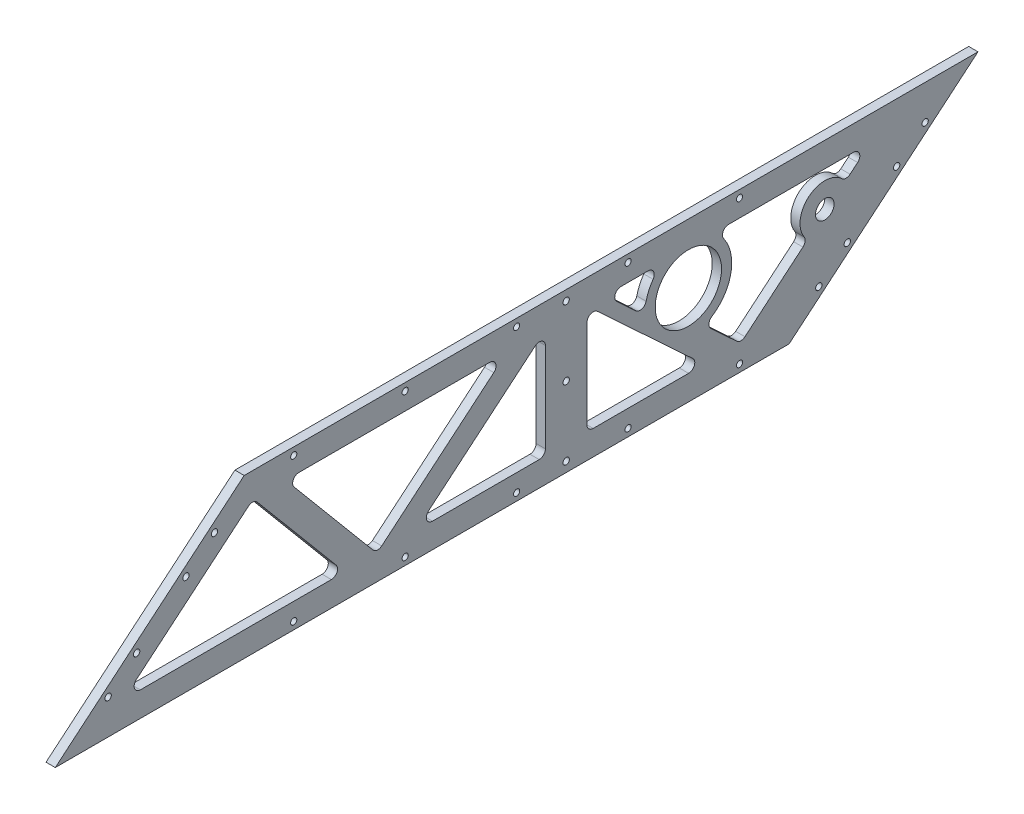
SolidWorks part; units mm, degrees
material "6061-T6 (SS)"
ref_plane "Front Plane" through (0, 0, 0) normal (0, 0, 1) x (1, 0, 0)
ref_plane "Top Plane" through (0, 0, 0) normal (0, 1, 0) x (1, 0, 0)
ref_plane "Right Plane" through (0, 0, 0) normal (1, 0, 0) x (0, 0, -1)
sketch "Sketch1" plane through (0, 0, 0) normal (1, 0, 0) x (0, 0, -1)
  line L0 (0, 12.7) -> (0, -12.7) construction
  line L1 (0, -12.7) -> (33.2976, -40.64) construction
  line L2 (33.2976, -40.64) -> (312.6976, -40.64)
  line L3 (312.6976, -40.64) -> (345.9952, -12.7)
  line L4 (345.9952, -12.7) -> (345.9952, 12.7) construction
  line L5 (345.9952, 12.7) -> (312.6976, 40.64) construction
  line L6 (312.6976, 40.64) -> (33.2976, 40.64)
  line L7 (33.2976, 40.64) -> (0, 12.7)
  line L8 (33.2976, 40.64) -> (33.2976, -40.64) construction
  line L9 (312.6976, 40.64) -> (312.6976, -40.64) construction
  line L10 (0, 0) -> (345.9952, 0) construction
  line L11 (0, 12.7) -> (-63.5681, -40.64)
  line L12 (-63.5681, -40.64) -> (33.2976, -40.64)
  line L13 (312.6976, 40.64) -> (409.5633, 40.64)
  line L14 (409.5633, 40.64) -> (345.9952, -12.7)
  point P10 (33.2976, 0)
  point P12 (312.6976, 0)
  dimension "D1" = 81.28
  dimension "D2" = 279.4
  dimension "D3" = 25.4
  dimension "D4" = 40
extrude "Boss-Extrude1" add sketch "Sketch1" along normal blind 4.7625
sketch "Sketch2" plane through (4.7625, 0, 0) normal (1, 0, 0) x (0, 0, -1)
  line L0 (-3.2177, 10) -> (373.048, 10) construction
  line L1 (312.6976, -40.64) -> (409.5633, 40.64) construction
  line L2 (345.048, 10) -> (245.048, 10) construction
  line L3 (245.048, -5) -> (345.048, -5) construction
  line L4 (245.048, -5) -> (245.048, 25) construction
  line L5 (245.048, 25) -> (345.048, 25) construction
  line L6 (345.048, -5) -> (345.048, 25) construction
  line L7 (33.2976, 40.64) -> (-63.5681, -40.64) construction
  line L9 (0, 0) -> (361.1305, 0) construction
  circle A0 centre (300.048, 10) radius 6.9977 construction
  circle A1 centre (282.2147, 8) radius 1.4986 construction
  circle A2 centre (270.2178, 15.9334) radius 0.9906 construction
  circle A3 centre (282.2147, 8) radius 11.4777 construction
  circle A4 centre (270.2178, 15.9334) radius 7.1501 construction
  circle A5 centre (300.048, 10) radius 12.827 construction
  circle A6 centre (261.048, 10) radius 17
  circle A7 centre (282.2147, 8) radius 5.1181 construction
  circle A8 centre (331.0042, 10) radius 4.7625
  point P11 (300.048, 10)
  point P12 (282.2147, 8)
  point P13 (270.2178, 15.9334)
  point P23 (261.048, 10)
  dimension "D5" = 13.9954
  dimension "D6" = 2.9972
  dimension "D7" = 1.9812
  dimension "D8" = 25.654
  dimension "D9" = 22.9553
  dimension "D10" = 14.3002
  dimension "D12" = 34
  dimension "D13" = 10.2362
  dimension "D17" = 9.525
  dimension "D1" = 17.9451
  dimension "D2" = 14.3828
  dimension "D3" = 30
  dimension "D4" = 100
  dimension "D11" = 10.922
  dimension "D14" = 16
  dimension "D15" = 13
  dimension "D16" = 55
  dimension "D18" = 30.9562
  dimension "D19" = 28
  dimension "D20" = 10
extrude "Gearbox (with Press fits)" cut sketch "Sketch2" against normal through all
sketch "Sketch3" plane through (4.7625, 0, 0) normal (1, 0, 0) x (0, 0, -1)
  line L0 (0, 0) -> (361.1305, 0) construction
  line L1 (28.757, 36.83) -> (405.0227, 36.83) construction
  line L2 (33.2976, 40.64) -> (-63.5681, -40.64) construction
  line L5 (409.5633, 40.64) -> (33.2976, 40.64) construction
  line L6 (312.6976, -40.64) -> (409.5633, 40.64) construction
  circle A0 centre (287.2976, 36.83) radius 1.5811
  circle A1 centre (230.1476, 36.83) radius 1.5811
  circle A2 centre (172.9976, 36.83) radius 1.5811
  circle A3 centre (115.8476, 36.83) radius 1.5811
  circle A4 centre (58.6976, 36.83) radius 1.5812
  circle A5 centre (58.6976, -36.83) radius 1.5812
  circle A6 centre (115.8476, -36.83) radius 1.5811
  circle A7 centre (172.9976, -36.83) radius 1.5811
  circle A8 centre (230.1476, -36.83) radius 1.5811
  circle A9 centre (287.2976, -36.83) radius 1.5811
  dimension "D1" = 3.1623
  dimension "D2" = 25.4
  dimension "D3" = 3.81
  dimension "D4" = 5
extrude "Cut-Extrude1" cut sketch "Sketch3" against normal through all
hole_wizard "#2 Clearance Hole1" positions "Sketch6" profile "Sketch5" hole size "#2" standard "ANSI Inch"
sketch "Sketch6" plane through (4.7625, 0, 0) normal (1, 0, 0) x (0, 0, -1)
  line L0 (241.1305, 40.64) -> (241.1305, -40.64) construction
  line L1 (409.5633, 40.64) -> (33.2976, 40.64) construction
  line L2 (-63.5681, -40.64) -> (312.6976, -40.64) construction
  line L4 (244.1305, 40.64) -> (244.1305, -40.64) construction
  line L6 (241.1305, -16) -> (342.0624, -16) construction
  line L7 (312.6976, -40.64) -> (409.5633, 40.64) construction
  line L9 (241.1305, -13) -> (345.6377, -13) construction
  line L11 (241.1305, 13) -> (376.6233, 13) construction
  line L12 (308.1305, 13) -> (308.1305, -13) construction
  circle A0 centre (257.1305, 0) radius 14 construction
  point P28 (267.1305, -13)
  point P30 (308.1305, -13)
  point P32 (244.1305, -13)
  point P34 (244.1305, 13)
  point P36 (275.1305, 13)
  point P38 (308.1305, 13)
  dimension "D1" = 3
  dimension "D2" = 3
  dimension "D3" = 26
  dimension "D4" = 29
  dimension "D5" = 16
  dimension "D6" = 16
  dimension "D7" = 67
  dimension "D8" = 34
sketch "Sketch5" plane through (4.7625, -13, -267.1305) normal (0, 1, 0) x (0, 0, -1)
  line L0 (0, 0) -> (0, 5.5586)
  line L1 (0, 5.5586) -> (1.2192, 4.826)
  line L2 (1.2192, 4.826) -> (1.2192, 0)
  line L5 (1.2192, 0) -> (0, 0)
  line L10 (0, 5.5586) -> (-1.2192, 4.826) construction
  line L11 (0, -6.35) -> (0, 107.95) construction
  dimension "Hole Dia." = 2.4384
  dimension "Hole Depth" = 4.826
  dimension "Drill Angle" = 118
hole_wizard "#4 Clearance Hole2" positions "Sketch8" profile "Sketch9" hole size "#4" standard "ANSI Inch"
sketch "Sketch8" plane through (4.7625, 0, 0) normal (1, 0, 0) x (0, 0, -1)
  line L0 (-15.1353, 0) -> (361.1305, 0) construction
  line L1 (33.2976, 40.64) -> (-63.5681, -40.64) construction
  line L2 (312.6976, -40.64) -> (409.5633, 40.64) construction
  line L4 (403.636, 40.64) -> (306.7703, -40.64) construction
  line L5 (409.5633, 40.64) -> (33.2976, 40.64) construction
  line L6 (-63.5681, -40.64) -> (312.6976, -40.64) construction
  line L8 (39.2249, 40.64) -> (-57.6408, -40.64) construction
  line L10 (355.2032, 0) -> (-9.208, 0) construction
  line L11 (327.9626, -22.8575) -> (-36.4485, -22.8575) construction
  line L13 (342.5558, -10.6124) -> (-21.8554, -10.6124) construction
  line L15 (3.4394, 10.6124) -> (367.8505, 10.6124) construction
  line L17 (18.0326, 22.8575) -> (382.4437, 22.8575) construction
  point P25 (327.9626, -22.8575)
  point P27 (342.5558, -10.6124)
  point P29 (367.8505, 10.6124)
  point P31 (382.4437, 22.8575)
  point P34 (-36.4485, -22.8575)
  point P36 (-21.8554, -10.6124)
  point P38 (3.4394, 10.6124)
  point P40 (18.0326, 22.8575)
  dimension "D1" = 16.51
  dimension "D2" = 19.05
  dimension "D3" = 16.51
  dimension "D4" = 19.05
  dimension "D5" = 3.81
  dimension "D6" = 3.81
sketch "Sketch9" plane through (4.7625, -22.8575, -327.9626) normal (0, 1, 0) x (0, 0, -1)
  line L0 (0, 0) -> (0, 29.6826)
  line L1 (0, 29.6826) -> (1.6319, 28.702)
  line L2 (1.6319, 28.702) -> (1.6319, 0)
  line L5 (1.6319, 0) -> (0, 0)
  line L10 (0, 29.6826) -> (-1.632, 28.702) construction
  line L11 (0, -6.35) -> (0, 107.95) construction
  dimension "Hole Dia." = 3.2639
  dimension "Hole Depth" = 28.702
  dimension "Drill Angle" = 118
hole_wizard "#4 Clearance Hole1" positions "Sketch11" profile "Sketch10" hole size "#4" standard "ANSI Inch"
sketch "Sketch11" plane through (4.7625, 0, 0) normal (1, 0, 0) x (0, 0, -1)
  line L0 (27.2435, 35.56) -> (403.5092, 35.56) construction
  line L1 (33.2976, 40.64) -> (-63.5681, -40.64) construction
  line L2 (312.6976, -40.64) -> (409.5633, 40.64) construction
  line L4 (-15.1353, 0) -> (361.1305, 0) construction
  line L5 (198.3976, 35.56) -> (198.3976, -35.56) construction
  line L6 (409.5633, 40.64) -> (33.2976, 40.64) construction
  point P12 (198.3976, 35.56)
  point P15 (198.3976, -35.56)
  point P20 (198.3976, 0)
  dimension "D1" = 5.08
  dimension "D2" = 165.1
sketch "Sketch10" plane through (4.7625, 35.56, -198.3976) normal (0, 1, 0) x (0, 0, -1)
  line L0 (0, 0) -> (0, 5.8066)
  line L1 (0, 5.8066) -> (1.6319, 4.826)
  line L2 (1.6319, 4.826) -> (1.6319, 0)
  line L5 (1.6319, 0) -> (0, 0)
  line L10 (0, 5.8066) -> (-1.6319, 4.826) construction
  line L11 (0, -6.35) -> (0, 107.95) construction
  dimension "Hole Dia." = 3.2639
  dimension "Hole Depth" = 4.826
  dimension "Drill Angle" = 118
sketch "Sketch12" plane through (4.7625, 0, 0) normal (1, 0, 0) x (0, 0, -1)
  line L0 (-21.9928, -22.3328) -> (35.4878, 25.8991)
  line L1 (39.9609, 25.5078) -> (80.4323, -22.7241)
  line L2 (78.0001, -27.94) -> (-19.9519, -27.94)
  line L3 (209.0547, 20.6605) -> (209.0547, -24.765)
  line L4 (58.8753, 22.7241) -> (99.3467, -25.5078)
  line L5 (103.8198, -25.8991) -> (161.3004, 22.3328)
  line L6 (159.2595, 27.94) -> (61.3075, 27.94)
  line L7 (127.8277, -22.3328) -> (182.5246, 23.5634)
  line L8 (212.2297, -27.94) -> (261.1643, -27.94)
  line L9 (187.7405, 21.1312) -> (187.7405, -24.765)
  line L10 (184.5655, -27.94) -> (129.8685, -27.94)
  line L11 (214.3898, 22.9875) -> (263.3244, -22.4381)
  line L12 (33.2976, 40.64) -> (-63.5681, -40.64) construction
  line L13 (-63.5681, -40.64) -> (312.6976, -40.64) construction
  line L14 (224.3152, 22.4381) -> (234.126, 13.3308)
  line L15 (18.1623, 27.94) -> (394.4281, 27.94) construction
  line L16 (312.6976, -40.64) -> (409.5633, 40.64) construction
  line L17 (409.5633, 40.64) -> (33.2976, 40.64) construction
  line L18 (-48.4329, -27.94) -> (327.8329, -27.94) construction
  line L19 (272.5922, -13.7128) -> (285.8644, -26.0333)
  line L20 (240.3803, 27.94) -> (226.4753, 27.94)
  line L21 (187.7405, 0) -> (198.3976, 0) construction
  line L22 (198.3976, 0) -> (209.0547, 0) construction
  line L23 (290.0654, -26.1385) -> (319.802, -1.1865)
  line L24 (281.7157, 27.94) -> (345.7904, 27.94)
  line L25 (347.8312, 22.3328) -> (343.966, 19.0895)
  circle A0 centre (261.048, 10) radius 22.225 construction
  circle A1 centre (198.3976, 0) radius 5.08 construction
  circle A2 centre (331.0042, 10) radius 12.7 construction
  circle A3 centre (198.3976, 35.56) radius 5.08 construction
  circle A4 centre (198.3976, -35.56) radius 5.08 construction
  arc A5 (161.3004, 22.3328) -> (159.2595, 27.94) centre (159.2595, 24.765) ccw
  arc A6 (58.8753, 22.7241) -> (61.3075, 27.94) centre (61.3075, 24.765) cw
  arc A7 (35.4878, 25.8991) -> (39.9609, 25.5078) centre (37.5287, 23.467) cw
  arc A8 (-21.9928, -22.3328) -> (-19.9519, -27.94) centre (-19.9519, -24.765) ccw
  arc A9 (80.4323, -22.7241) -> (78.0001, -27.94) centre (78.0001, -24.765) cw
  arc A10 (99.3467, -25.5078) -> (103.8198, -25.8991) centre (101.7789, -23.467) ccw
  arc A11 (127.8277, -22.3328) -> (129.8685, -27.94) centre (129.8685, -24.765) ccw
  arc A12 (187.7405, -24.765) -> (184.5655, -27.94) centre (184.5655, -24.765) cw
  arc A13 (182.5246, 23.5634) -> (187.7405, 21.1312) centre (184.5655, 21.1312) cw
  arc A14 (239.3814, 14.9505) -> (242.9637, 22.9194) centre (261.048, 10) cw
  arc A15 (261.1643, -27.94) -> (263.3244, -22.4381) centre (261.1643, -24.765) ccw
  arc A16 (209.0547, -24.765) -> (212.2297, -27.94) centre (212.2297, -24.765) ccw
  arc A17 (209.0547, 20.6605) -> (214.3898, 22.9875) centre (212.2297, 20.6605) cw
  arc A18 (234.126, 13.3308) -> (239.3814, 14.9505) centre (236.2861, 15.6577) ccw
  arc A19 (224.3152, 22.4381) -> (226.4753, 27.94) centre (226.4753, 24.765) cw
  arc A20 (242.9637, 22.9194) -> (240.3803, 27.94) centre (240.3803, 24.765) ccw
  arc A21 (273.0392, -8.7126) -> (279.1323, 22.9194) centre (261.048, 10) ccw
  arc A22 (320.4098, 2.9966) -> (339.7409, 19.2173) centre (331.0042, 10) cw
  arc A23 (345.7904, 27.94) -> (347.8312, 22.3328) centre (345.7904, 24.765) cw
  arc A24 (339.7409, 19.2173) -> (343.966, 19.0895) centre (341.9251, 21.5217) ccw
  arc A25 (319.802, -1.1865) -> (320.4098, 2.9966) centre (317.7612, 1.2457) ccw
  arc A26 (285.8644, -26.0333) -> (290.0654, -26.1385) centre (288.0245, -23.7063) ccw
  arc A27 (272.5922, -13.7128) -> (273.0392, -8.7126) centre (274.7523, -11.3858) cw
  arc A28 (279.1323, 22.9194) -> (281.7157, 27.94) centre (281.7157, 24.765) cw
  point P39 (167.9828, 27.94)
  point P44 (37.92, 27.94)
  point P51 (101.3876, -27.94)
  point P57 (187.7405, 27.94)
  point P70 (269.2513, -27.94)
  point P73 (209.0547, -27.94)
  point P76 (209.0547, 27.94)
  point P77 (238.8479, 8.9475)
  point P82 (218.3883, 27.94)
  point P83 (247.929, 27.94)
  point P92 (354.5136, 27.94)
  point P95 (341.5561, 17.0673)
  point P98 (322.2119, 0.8356)
  point P101 (287.9184, -27.94)
  point P104 (269.2846, -10.6424)
  point P107 (274.167, 27.94)
  dimension "D1" = 44.45
  dimension "D2" = 10.16
  dimension "D3" = 25.4
  dimension "D4" = 10.16
  dimension "D5" = 10.16
  dimension "D11" = 3.175
  dimension "D12" = 3.175
  dimension "D14" = 3.175
  dimension "D15" = 3.175
  dimension "D16" = 3.175
  dimension "D17" = 3.175
  dimension "D19" = 3.175
  dimension "D6" = 12.7
  dimension "D7" = 12.7
  dimension "D8" = 12.7
  dimension "D9" = 12.7
  dimension "D10" = 12.7
  dimension "D13" = 6.35
  dimension "D18" = 12.7
extrude "Cut-Extrude2" cut sketch "Sketch12" against normal through all
